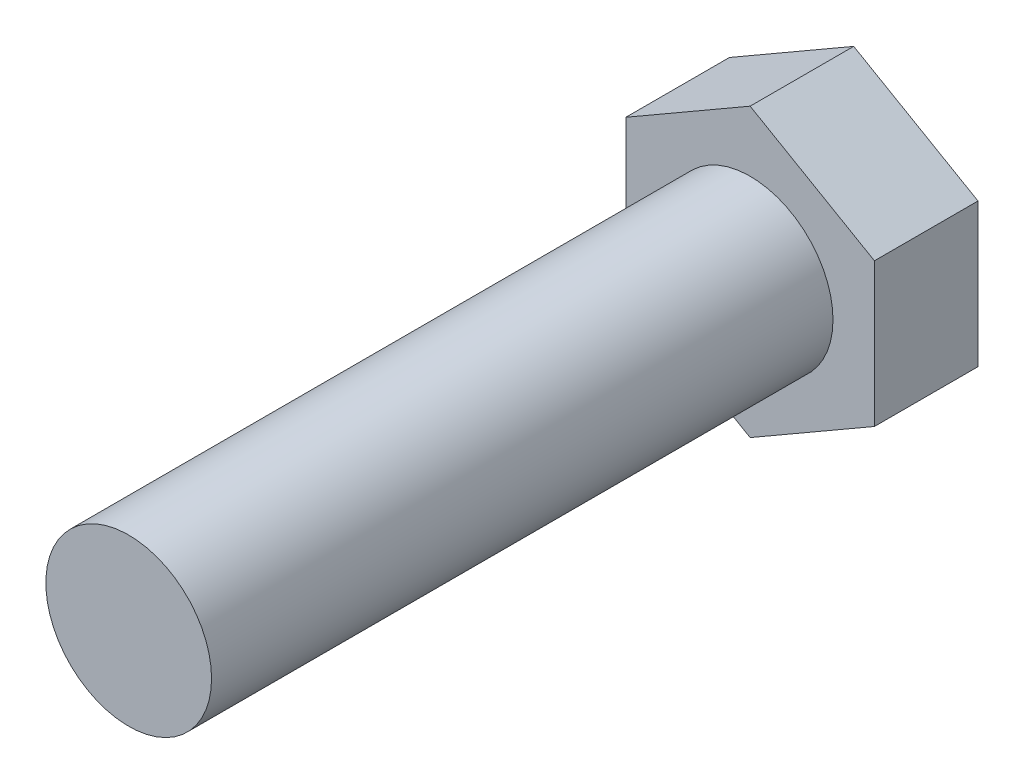
SolidWorks part; units mm, degrees
material "Alloy Steel (SS)"
ref_plane "Front Plane" through (0, 0, 0) normal (0, 0, 1) x (1, 0, 0)
ref_plane "Top Plane" through (0, 0, 0) normal (0, 1, 0) x (1, 0, 0)
ref_plane "Right Plane" through (0, 0, 0) normal (1, 0, 0) x (0, 0, -1)
sketch "Sketch1" plane through (0, 0, 0) normal (0, 0, 1) x (1, 0, 0)
  line L0 (0, 0) -> (0, 6.9282) construction
  line L2 (0, 6.9282) -> (-6, 3.4641)
  line L3 (-6, 3.4641) -> (-6, -3.4641)
  line L4 (-6, -3.4641) -> (0, -6.9282)
  line L5 (0, -6.9282) -> (6, -3.4641)
  line L6 (6, -3.4641) -> (6, 3.4641)
  line L7 (6, 3.4641) -> (0, 6.9282)
  circle A0 centre (0, 0) radius 6 construction
  circle A1 centre (0, 0) radius 4 construction
  dimension "D1" = 8
  dimension "D2" = 2
extrude "Boss-Extrude1" add sketch "Sketch1" along normal blind 5
sketch "Sketch2" plane through (0, 0, 5) normal (0, 0, 1) x (1, 0, 0)
  circle A0 centre (0, 0) radius 4
  circle A1 centre (0, 0) radius 4 construction
extrude "Boss-Extrude2" add sketch "Sketch2" along normal blind 30
cosmetic thread "Cosmetic Thread1" parameters "D1"=7, "D2"=6.891
